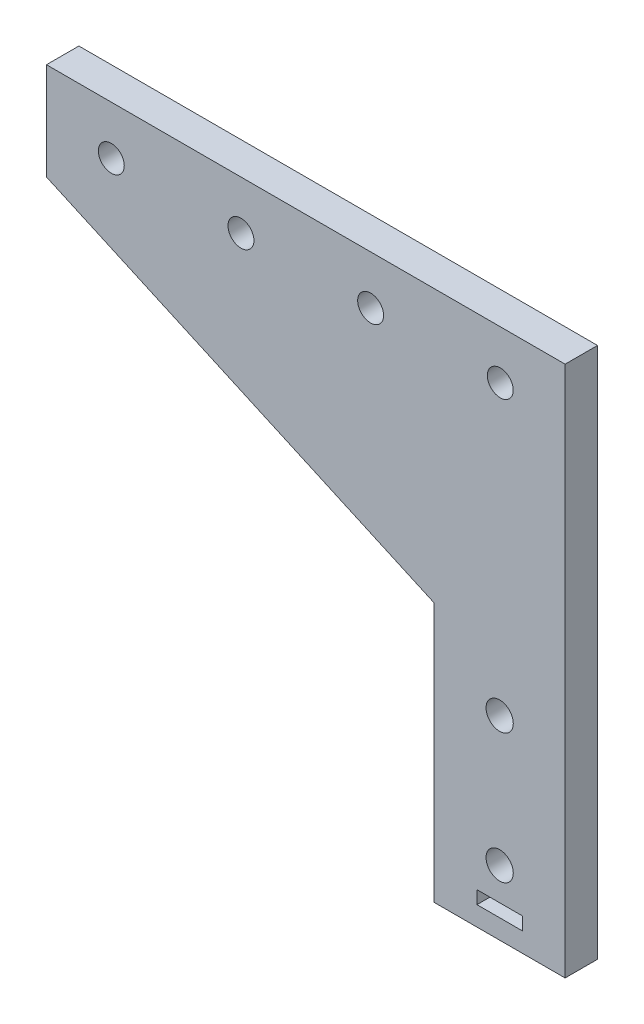
SolidWorks part; units mm, degrees
ref_plane "Front Plane" through (0, 0, 0) normal (0, 0, 1) x (1, 0, 0)
ref_plane "Top Plane" through (0, 0, 0) normal (0, 1, 0) x (1, 0, 0)
ref_plane "Right Plane" through (0, 0, 0) normal (1, 0, 0) x (0, 0, -1)
sketch "Sketch1" plane through (0, 0, 0) normal (0, 0, 1) x (1, 0, 0)
  line L0 (0, 0) -> (0, 82)
  line L1 (0, 0) -> (-20.1916, 0)
  line L2 (-20.1916, 0) -> (-20.1916, 40)
  line L4 (-80, 82) -> (0, 82)
  line L5 (-80, 82) -> (-80, 67)
  line L6 (-80, 67) -> (-20.1916, 40)
  line L7 (-10.0958, 43.1953) -> (-10.0958, -28.1776) construction
  line L8 (-87.8856, 74.5) -> (42.7721, 74.5) construction
  line L10 (-13.5958, 5) -> (-6.5958, 5)
  line L11 (-13.5958, 5) -> (-13.5958, 3)
  line L12 (-13.5958, 3) -> (-6.5958, 3)
  line L13 (-6.5958, 5) -> (-6.5958, 3)
  circle A0 centre (-10.0958, 10) radius 2.1
  circle A1 centre (-10.0958, 30) radius 2.1
  circle A2 centre (-70, 74.5) radius 2
  circle A3 centre (-50, 74.5) radius 2
  circle A4 centre (-30, 74.5) radius 2
  circle A5 centre (-10, 74.5) radius 2
  point P9 (-10.0958, 0)
  point P16 (-80, 74.5)
  point P29 (-10.0958, 5)
  point P30 (-10.0958, 3)
  dimension "D5" = 10
  dimension "D7" = 10
  dimension "D1" = 82
  dimension "D2" = 15
  dimension "D3" = 40
  dimension "D4" = 80
  dimension "D6" = 20
  dimension "D9" = 7
  dimension "D10" = 2
  dimension "D11" = 3
  dimension "D8" = 4
extrude "Boss-Extrude1" add sketch "Sketch1" along normal blind 5
